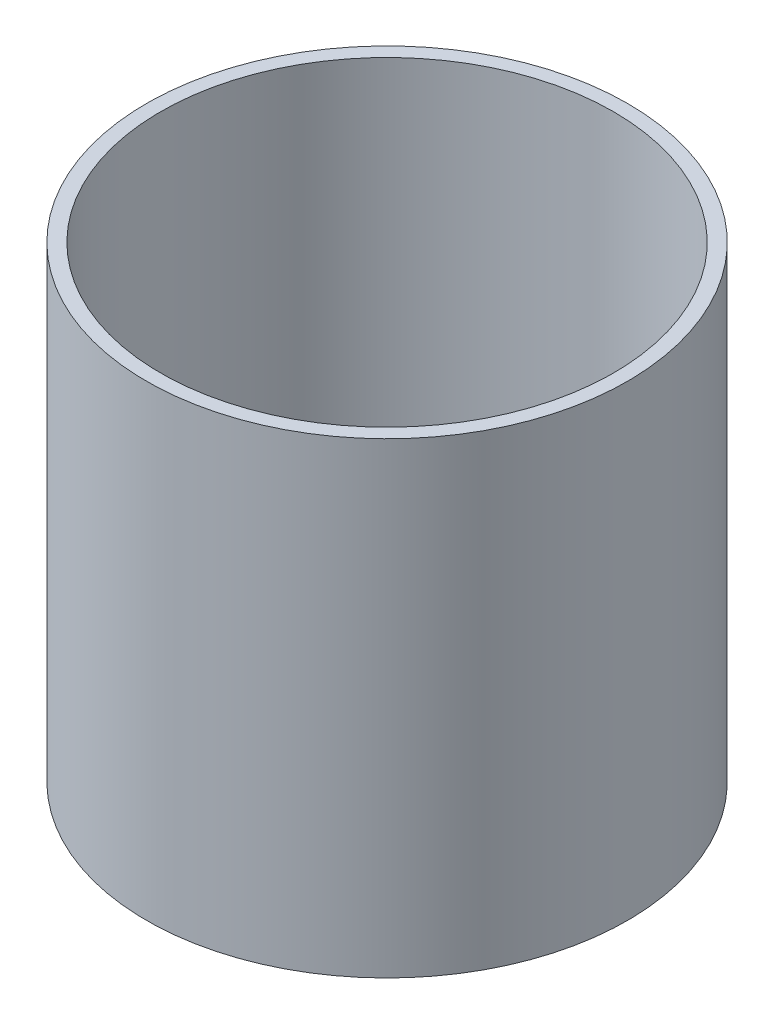
SolidWorks part; units mm, degrees
ref_plane "Front Plane" through (0, 0, 0) normal (0, 0, 1) x (1, 0, 0)
ref_plane "Top Plane" through (0, 0, 0) normal (0, 1, 0) x (1, 0, 0)
ref_plane "Right Plane" through (0, 0, 0) normal (1, 0, 0) x (0, 0, -1)
sketch "Compartment" plane through (0, 0, 0) normal (0, 0, 1) x (1, 0, 0)
  line L3 (85, -80) -> (0, -80)
  line L6 (80, 85) -> (85, 85)
  line L9 (80, 85) -> (80, -75)
  line L10 (80, -75) -> (0, -75)
  line L11 (0, -75) -> (0, -80)
  line L14 (85, 85) -> (85, -80)
  dimension "D1" = 160
  dimension "D2" = 5
  dimension "D5" = 80
  dimension "D6" = 5
  dimension "D9" = 80
ref_axis "Axis1" through (0, 0, 0) along (0, 1, 0)
revolve "Revolve1" add sketch "Compartment" angle 360 about axis through (0, 0, 0) along (0, 1, 0)
sketch "Motor Hole" plane through (0, -80, 0) normal (0, -1, 0) x (1, 0, 0)
  circle A0 centre (0, 0) radius 12.5
  dimension "D1" = 25
extrude "Cut-Extrude2" cut sketch "Motor Hole" against normal up to next
